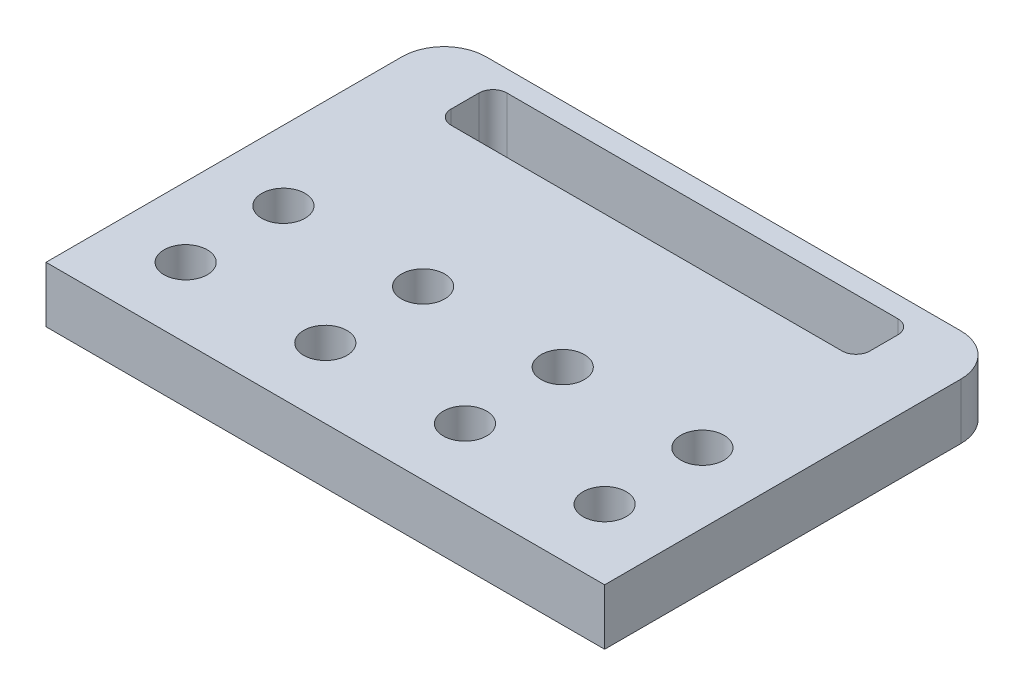
SolidWorks part; units mm, degrees
material "VMA 碳纤维"
ref_plane "前视基准面" through (0, 0, 0) normal (0, 0, 1) x (1, 0, 0)
ref_plane "上视基准面" through (0, 0, 0) normal (0, 1, 0) x (1, 0, 0)
ref_plane "右视基准面" through (0, 0, 0) normal (1, 0, 0) x (0, 0, -1)
other "Configuration Table"
sketch "草图1" plane through (0, 0, 0) normal (0, 1, 0) x (1, 0, 0)
  line L0 (-20, 3.75) -> (20, 3.75) construction
  line L1 (-20, -14.25) -> (20, -14.25)
  line L2 (-20, -14.25) -> (-20, 14.25)
  line L3 (-20, 14.25) -> (20, 14.25)
  line L4 (20, -14.25) -> (20, 14.25)
  line L5 (-20, -14.25) -> (20, 14.25) construction
  line L6 (-20, 14.25) -> (20, -14.25) construction
  line L7 (-20, 0.75) -> (20, 0.75) construction
  line L8 (0, 0) -> (0, 8.75) construction
  line L9 (-14, 12.75) -> (14, 12.75)
  line L10 (-15, 11.75) -> (-15, 9.75)
  line L11 (-14, 8.75) -> (14, 8.75)
  line L12 (15, 11.75) -> (15, 9.75)
  arc A0 (14, 12.75) -> (15, 11.75) centre (14, 11.75) cw
  arc A1 (14, 8.75) -> (15, 9.75) centre (14, 9.75) ccw
  arc A2 (-15, 9.75) -> (-14, 8.75) centre (-14, 9.75) ccw
  arc A3 (-14, 12.75) -> (-15, 11.75) centre (-14, 11.75) ccw
  point P0 (0, 0)
  point P19 (15, 12.75)
  point P22 (15, 8.75)
  point P27 (-15, 12.75)
  dimension "D7" = 1
  dimension "D1" = 40
  dimension "D2" = 10.5
  dimension "D3" = 3
  dimension "D4" = 5
  dimension "D5" = 4
  dimension "D6" = 30
  dimension "D8" = 15
extrude "凸台-拉伸1" add sketch "草图1" along normal blind 4
sketch "草图2" plane through (0, 4, 0) normal (0, 1, 0) x (1, 0, 0)
  line L0 (-20, -9.25) -> (-15, -9.25) construction
  line L1 (-20, 14.25) -> (-20, -14.25) construction
  line L2 (-15, -9.25) -> (5, -9.25) construction
  line L3 (-20, -14.25) -> (20, -14.25) construction
  line L4 (-15, -9.25) -> (-5, -9.25) construction
  line L5 (0, -16.1626) -> (0, 0) construction
  circle A0 centre (-15, -9.25) radius 1.55
  circle A1 centre (5, -9.25) radius 1.55
  circle A2 centre (15, -9.25) radius 1.55
  circle A3 centre (-5, -9.25) radius 1.55
  dimension "D4" = 3.1
  dimension "D3" = 5
  dimension "D5" = 5
  dimension "D7" = 10
  dimension "D1" = 2
extrude "切除-拉伸1" cut sketch "草图2" against normal through all
sketch "草图3" plane through (0, 4, 0) normal (0, 1, 0) x (1, 0, 0)
  line L0 (-20, -2.25) -> (20, -2.25) construction
  line L1 (-20, 14.25) -> (-20, -14.25) construction
  line L2 (20, -14.25) -> (20, 14.25) construction
  line L3 (20, 14.25) -> (-20, 14.25) construction
  line L4 (-20, -5.25) -> (20, -5.25) construction
  line L5 (-15, -2.25) -> (-5, -2.25) construction
  circle A0 centre (-15, -2.25) radius 1.55
  circle A2 centre (-5, -2.25) radius 1.55
  circle A3 centre (5, -2.25) radius 1.55
  circle A4 centre (15, -2.25) radius 1.55
  dimension "D3" = 3.1
  dimension "D5" = 4
  dimension "D6" = 10
  dimension "D1" = 16.5
  dimension "D2" = 5
  dimension "D4" = 3
extrude "切除-拉伸2" cut sketch "草图3" against normal through all
fillet "圆角1" radius 3 2 edges at (20, 2, -14.25) (-20, 2, -14.25)
